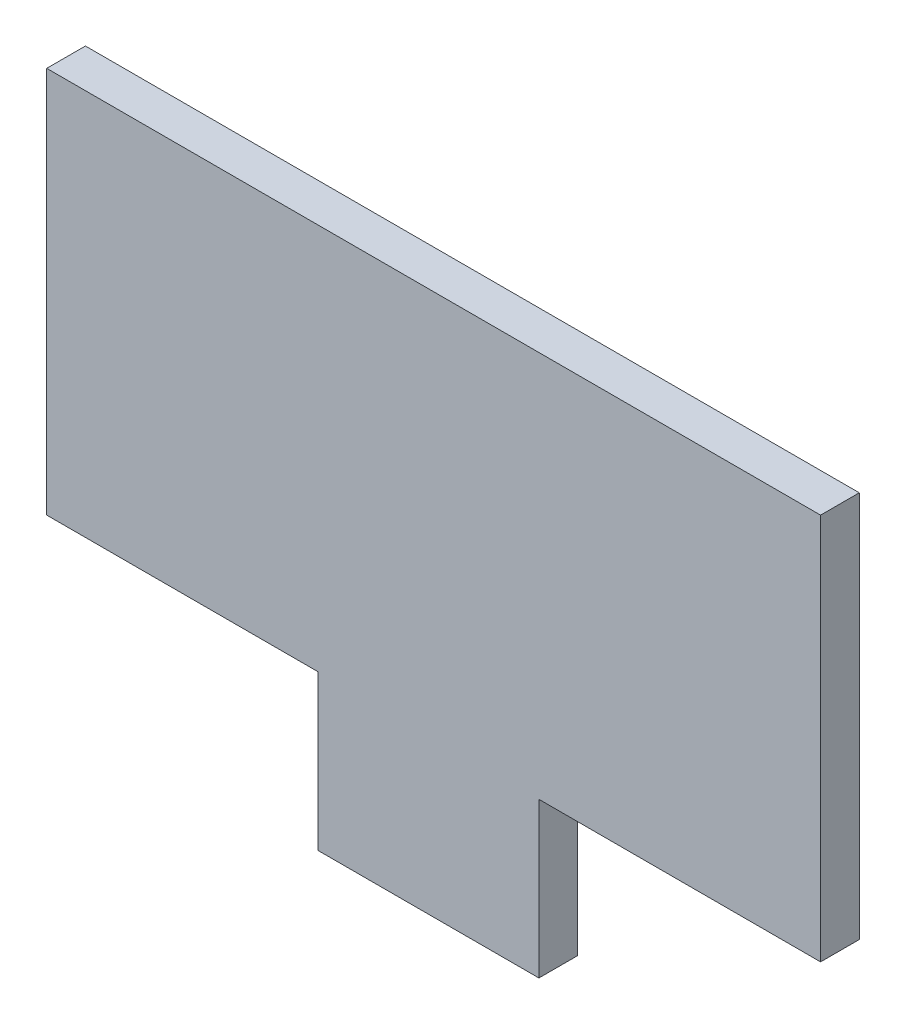
SolidWorks part; units mm, degrees
ref_plane "Front Plane" through (0, 0, 0) normal (0, 0, 1) x (1, 0, 0)
ref_plane "Top Plane" through (0, 0, 0) normal (0, 1, 0) x (1, 0, 0)
ref_plane "Right Plane" through (0, 0, 0) normal (1, 0, 0) x (0, 0, -1)
sketch "Sketch1" plane through (0, 0, 0) normal (0, 0, 1) x (1, 0, 0)
  line L1 (1.2195, 25.2814) -> (51.2195, 25.2814)
  line L2 (1.2195, 25.2814) -> (1.2195, 0.2814)
  line L3 (1.2195, 0.2814) -> (51.2195, 0.2814)
  line L4 (51.2195, 25.2814) -> (51.2195, 0.2814)
  line L5 (18.7617, 0.2814) -> (33.0206, 0.2814)
  line L6 (18.7617, 0.2814) -> (18.7617, -9.7186)
  line L7 (18.7617, -9.7186) -> (33.0206, -9.7186)
  line L8 (33.0206, 0.2814) -> (33.0206, -9.7186)
  dimension "D1" = 25
  dimension "D2" = 50
  dimension "D3" = 10
extrude "Boss-Extrude1" add sketch "Sketch1" along normal blind 2.5 contours L4 L1 L2 L3 | L8 L3 L6 L7
